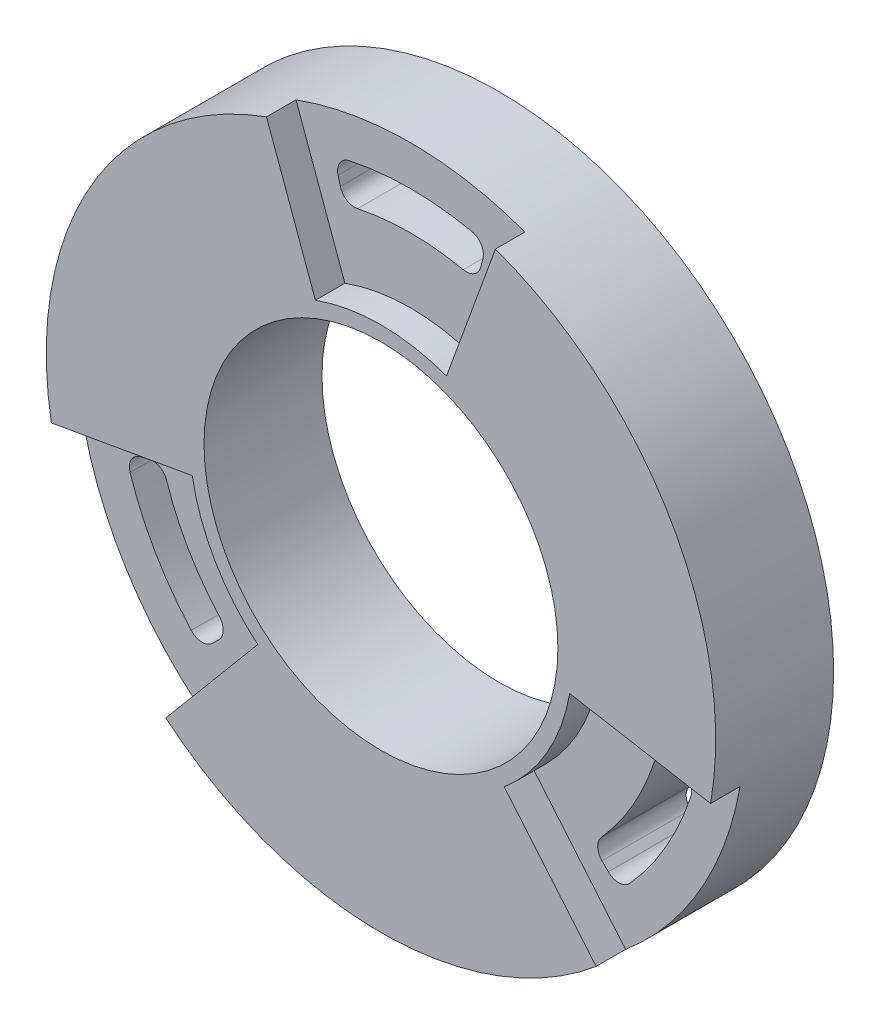
SolidWorks part; units mm, degrees
ref_plane "Alzado" through (0, 0, 0) normal (0, 0, 1) x (1, 0, 0)
ref_plane "Planta" through (0, 0, 0) normal (0, 1, 0) x (1, 0, 0)
ref_plane "Vista lateral" through (0, 0, 0) normal (1, 0, 0) x (0, 0, -1)
sketch "Croquis1" plane through (0, 0, 0) normal (0, 0, 1) x (1, 0, 0)
  line L0 (0, 0) -> (0, 9.1377) construction
  line L1 (2.3776, 8.8734) -> (2.4554, 9.1636)
  line L2 (8.8734, -2.3776) -> (9.1636, -2.4554)
  line L3 (-2.3776, 8.8734) -> (-2.4554, 9.1636)
  line L4 (6.4958, -6.4958) -> (6.7082, -6.7082)
  line L5 (-6.4958, -6.4958) -> (-6.7082, -6.7082)
  line L6 (-8.8734, -2.3776) -> (-9.1636, -2.4554)
  circle A0 centre (0, 0) radius 11.35
  circle A1 centre (0, 0) radius 6
  arc A2 (2.0762, 9.7821) -> (-2.0762, 9.7821) centre (0, 0) ccw
  arc A3 (1.7917, 8.5135) -> (-1.7917, 8.5135) centre (0, 0) ccw
  arc A4 (1.7917, 8.5135) -> (2.3776, 8.8734) centre (1.8947, 9.0028) ccw
  arc A5 (2.4554, 9.1636) -> (2.0762, 9.7821) centre (1.9724, 9.293) ccw
  arc A6 (-1.7917, 8.5135) -> (-2.3776, 8.8734) centre (-1.8947, 9.0028) cw
  arc A7 (-2.4554, 9.1636) -> (-2.0762, 9.7821) centre (-1.9724, 9.293) cw
  arc A8 (8.2688, -2.7051) -> (8.8734, -2.3776) centre (8.744, -2.8606) cw
  arc A9 (9.1636, -2.4554) -> (9.5096, -3.093) centre (9.0342, -2.9383) cw
  arc A10 (7.4334, -6.6891) -> (9.5096, -3.093) centre (0, 0) ccw
  arc A11 (6.4771, -5.8084) -> (8.2688, -2.7051) centre (0, 0) ccw
  arc A12 (6.4771, -5.8084) -> (6.4958, -6.4958) centre (6.8493, -6.1422) ccw
  arc A13 (6.7082, -6.7082) -> (7.4334, -6.6891) centre (7.0618, -6.3547) ccw
  arc A14 (-6.4771, -5.8084) -> (-6.4958, -6.4958) centre (-6.8493, -6.1422) cw
  arc A15 (-6.7082, -6.7082) -> (-7.4334, -6.6891) centre (-7.0618, -6.3547) cw
  arc A16 (-9.5096, -3.093) -> (-7.4334, -6.6891) centre (0, 0) ccw
  arc A17 (-8.2688, -2.7051) -> (-6.4771, -5.8084) centre (0, 0) ccw
  arc A18 (-8.2688, -2.7051) -> (-8.8734, -2.3776) centre (-8.744, -2.8606) ccw
  arc A19 (-9.1636, -2.4554) -> (-9.5096, -3.093) centre (-9.0342, -2.9383) ccw
  point P44 (0, 0)
  dimension "D1" = 22.7
  dimension "D2" = 12
  dimension "D3" = 20
  dimension "D4" = 17.4
  dimension "D6" = 0.5
  dimension "D5" = 15
  dimension "D7" = 3
extrude "Saliente-Extruir1" add sketch "Croquis1" along normal blind 4
sketch "Croquis2" plane through (0, 0, 4) normal (0, 0, 1) x (1, 0, 0)
  line L0 (0, 0) -> (0, 4.1471) construction
  line L1 (2.2231, 6.108) -> (3.8819, 10.6655)
  line L2 (-2.2231, 6.108) -> (-3.8819, 10.6655)
  line L3 (6.4013, -1.1287) -> (11.1776, -1.9709)
  line L4 (4.1781, -4.9793) -> (7.2956, -8.6946)
  line L5 (-4.1781, -4.9793) -> (-7.2956, -8.6946)
  line L6 (-6.4013, -1.1287) -> (-11.1776, -1.9709)
  arc A0 (2.2231, 6.108) -> (-2.2231, 6.108) centre (0, 0) ccw
  arc A1 (3.8819, 10.6655) -> (-3.8819, 10.6655) centre (0, 0) ccw
  arc A2 (7.2956, -8.6946) -> (11.1776, -1.9709) centre (0, 0) ccw
  arc A3 (4.1781, -4.9793) -> (6.4013, -1.1287) centre (0, 0) ccw
  arc A4 (-11.1776, -1.9709) -> (-7.2956, -8.6946) centre (0, 0) ccw
  arc A5 (-6.4013, -1.1287) -> (-4.1781, -4.9793) centre (0, 0) ccw
  point P18 (0, 0)
  dimension "D1" = 13
  dimension "D2" = 20
  dimension "D3" = 20
  dimension "D4" = 3
extrude "Cortar-Extruir1" cut sketch "Croquis2" against normal blind 1
